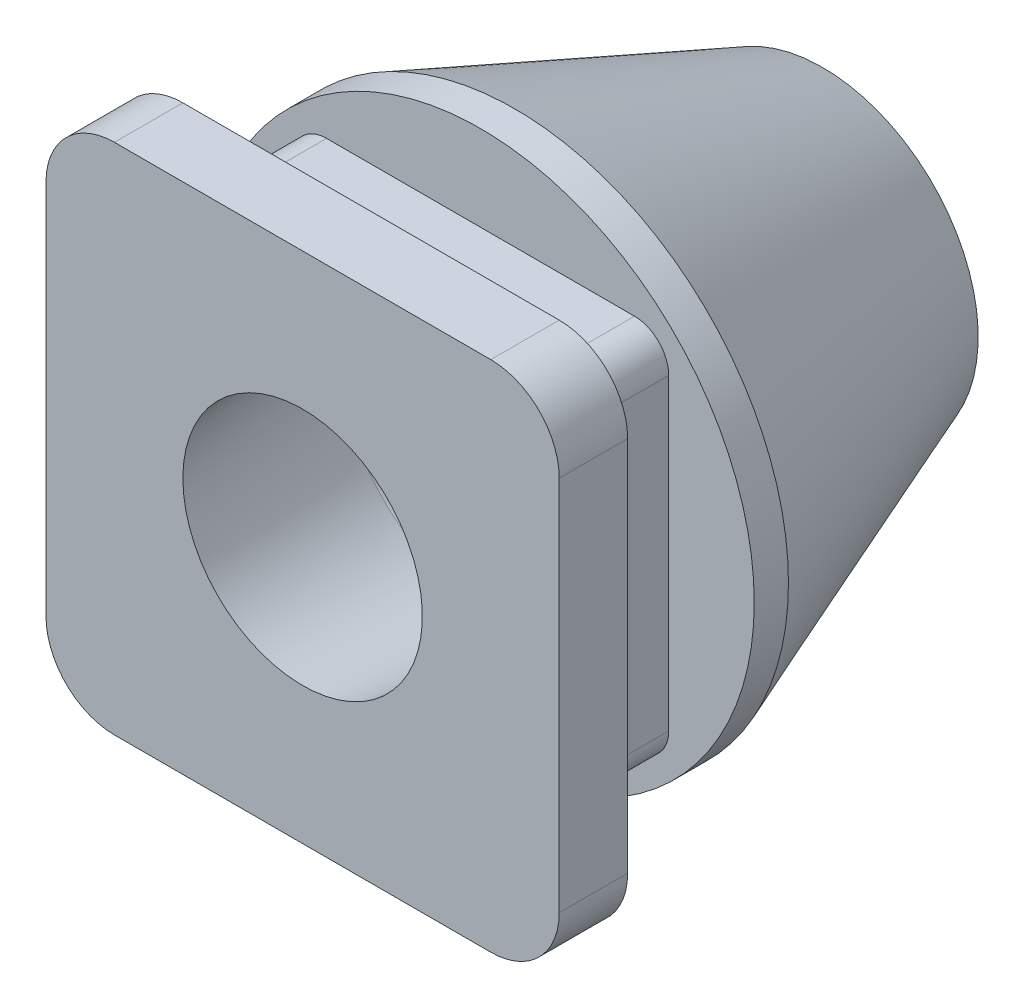
SolidWorks part; units mm, degrees
ref_plane "Front Plane" through (0, 0, 0) normal (0, 0, 1) x (1, 0, 0)
ref_plane "Top Plane" through (0, 0, 0) normal (0, 1, 0) x (1, 0, 0)
ref_plane "Right Plane" through (0, 0, 0) normal (1, 0, 0) x (0, 0, -1)
sketch "Sketch1" plane through (0, 0, 0) normal (0, 0, 1) x (1, 0, 0)
  line L1 (-7.5, -7.5) -> (7.5, -7.5)
  line L2 (-7.5, -7.5) -> (-7.5, 7.5)
  line L3 (-7.5, 7.5) -> (7.5, 7.5)
  line L4 (7.5, -7.5) -> (7.5, 7.5)
  line L5 (-7.5, -7.5) -> (7.5, 7.5) construction
  line L6 (-7.5, 7.5) -> (7.5, -7.5) construction
  circle A0 centre (0, 0) radius 4
  circle A1 centre (0, 0) radius 5.5 construction
  dimension "D1" = 8
  dimension "D2" = 1.5
  dimension "D3" = 15
extrude "Boss-Extrude1" add sketch "Sketch1" along normal blind 2
sketch "Sketch2" plane through (0, 0, 0) normal (0, 0, -1) x (-1, 0, 0)
  line L1 (-5.5, 5.5) -> (5.5, 5.5)
  line L2 (-5.5, 5.5) -> (-5.5, -5.5)
  line L3 (-5.5, -5.5) -> (5.5, -5.5)
  line L4 (5.5, 5.5) -> (5.5, -5.5)
  line L5 (-5.5, 5.5) -> (5.5, -5.5) construction
  line L6 (-5.5, -5.5) -> (5.5, 5.5) construction
  circle A0 centre (0, 0) radius 4
  dimension "D1" = 8
  dimension "D2" = 11
extrude "Boss-Extrude2" add sketch "Sketch2" along normal blind 3.2
sketch "Sketch3" plane through (0, 0, -3.2) normal (0, 0, -1) x (-1, 0, 0)
  circle A0 centre (0, 0) radius 4
  circle A1 centre (0, 0) radius 8
  dimension "D1" = 8
  dimension "D2" = 16
extrude "Boss-Extrude3" add sketch "Sketch3" along normal blind 10
sketch "Sketch4" plane through (0, 0, 0) normal (0, 1, 0) x (1, 0, 0)
  line L0 (-4, 3.2) -> (-4, -2)
  line L1 (-8, 3.2) -> (8, 3.2) construction
  line L4 (-4, -2) -> (-3.5, -2)
  line L5 (-5.5, 3.2) -> (-4, 3.2) construction
  line L7 (-3.5, -2) -> (-4, 3.2)
  line L8 (0, 13.2) -> (0, -2) construction
  line L9 (4, 13.2) -> (-4, 13.2) construction
  line L10 (-7.5, -2) -> (7.5, -2) construction
  line L11 (-4, -2) -> (4, -2) construction
  point P4 (-5.5043, 3.2)
  point P5 (-5.4862, 3.2)
  point P8 (-5.5, 3.2)
  dimension "D1" = 1.5
  dimension "D2" = 0.5
revolve "Revolve1" add sketch "Sketch4" angle 360 about L8
chamfer "Chamfer1" distance 9 angle 21 1 edges at (-8, 0, -13.2)
fillet "Fillet1" radius 2 4 edges at (7.5, -7.5, 1) (-7.5, -7.5, 1) (-7.5, 7.5, 1) (7.5, 7.5, 1)
fillet "Fillet2" radius 1 4 edges at (-5.5, -5.5, -1.6) (5.5, -5.5, -1.6) (5.5, 5.5, -1.6) (-5.5, 5.5, -1.6)
